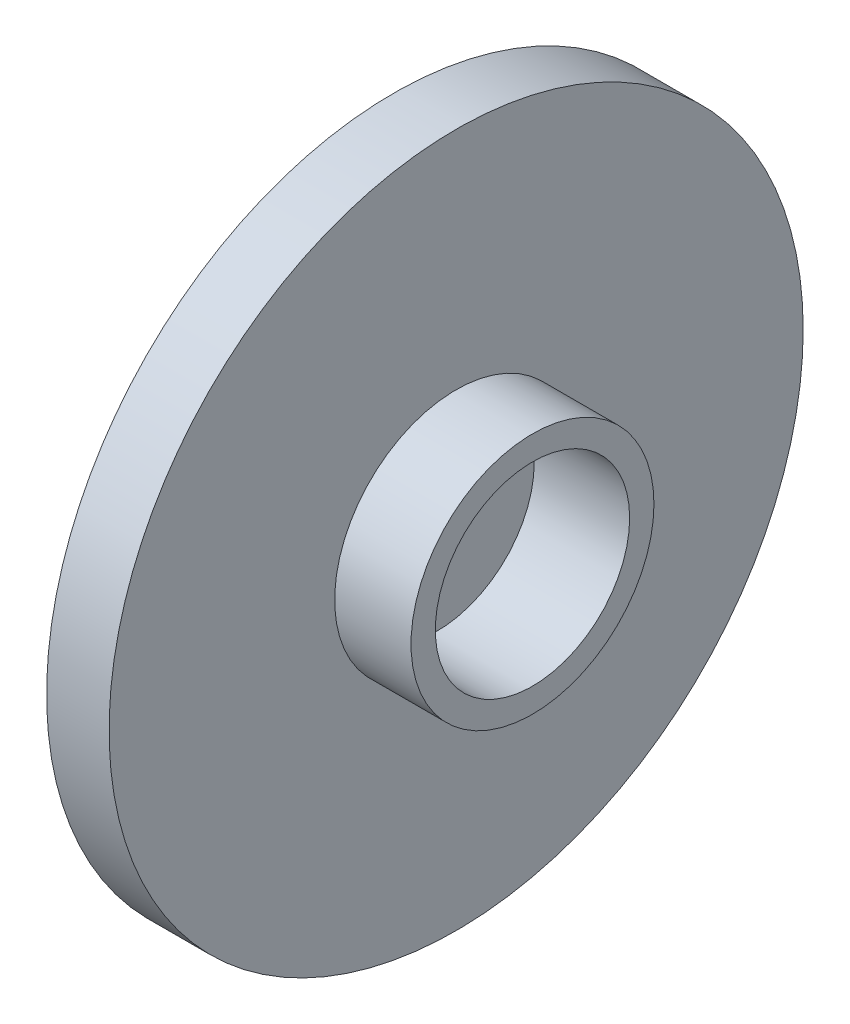
SolidWorks part; units mm, degrees
ref_plane "Front Plane" through (0, 0, 0) normal (0, 0, 1) x (1, 0, 0)
ref_plane "Top Plane" through (0, 0, 0) normal (0, 1, 0) x (1, 0, 0)
ref_plane "Right Plane" through (0, 0, 0) normal (1, 0, 0) x (0, 0, -1)
sketch "Sketch2" plane through (0, 0, 0) normal (0, 1, 0) x (1, 0, 0)
  line L0 (-2.75, 1) -> (-3.6, 1)
  line L1 (-3.6, 1) -> (-3.6, 2.25)
  line L3 (-2.2, 10) -> (-2.2, 3.5)
  line L5 (0, 3.5) -> (0, 2.8)
  line L7 (0, 2.8) -> (-2.75, 2.8)
  line L9 (-2.75, 2.8) -> (-2.75, 1)
  line L10 (0, 0) -> (-3.6, 0) construction
  line L11 (-3.6, 0) -> (-3.6, 1) construction
  line L12 (-4, 10) -> (-2.2, 10)
  line L13 (-3.6, 2.25) -> (-4.6, 2.25)
  line L14 (-4.6, 2.25) -> (-4.6, 2.8)
  line L15 (-4.6, 2.8) -> (-4, 2.8)
  line L16 (-4, 2.8) -> (-4, 10)
  line L17 (-2.2, 3.5) -> (0, 3.5)
  dimension "D1" = 1.8
  dimension "D2" = 10
  dimension "D3" = 7
  dimension "D4" = 4.6
  dimension "D5" = 1
  dimension "D6" = 4
  dimension "D7" = 1
  dimension "D8" = 5.6
  dimension "D9" = 4.5
  dimension "D10" = 5.6
  dimension "D11" = 2.75
revolve "Revolve1" add sketch "Sketch2" angle 360 about L10
sketch "Sketch3" [suppressed] plane through (-4, 0, 0) normal (-1, 0, 0) x (0, 0, 1)
  line L0 (3.4202, -9.3969) -> (-2.6619, -2.2725)
  line L1 (-2.6619, 2.2725) -> (3.4202, 9.3969)
  line L2 (3.4202, 9.3969) -> (3.4202, -9.3969) construction
  line L3 (0, 0) -> (3.4202, -9.3969) construction
  line L4 (3.4202, 9.3969) -> (0, 0) construction
  circle A0 centre (0, 0) radius 3.5 construction
  arc A1 (-2.6619, 2.2725) -> (-2.6619, -2.2725) centre (0, 0) ccw
  circle A2 centre (0, 0) radius 10 construction
  arc A3 (3.4202, 9.3969) -> (3.4202, -9.3969) centre (0, 0) ccw
  dimension "D1" = 140
extrude "Cut-Extrude1" [suppressed] cut sketch "Sketch3" against normal blind 10
